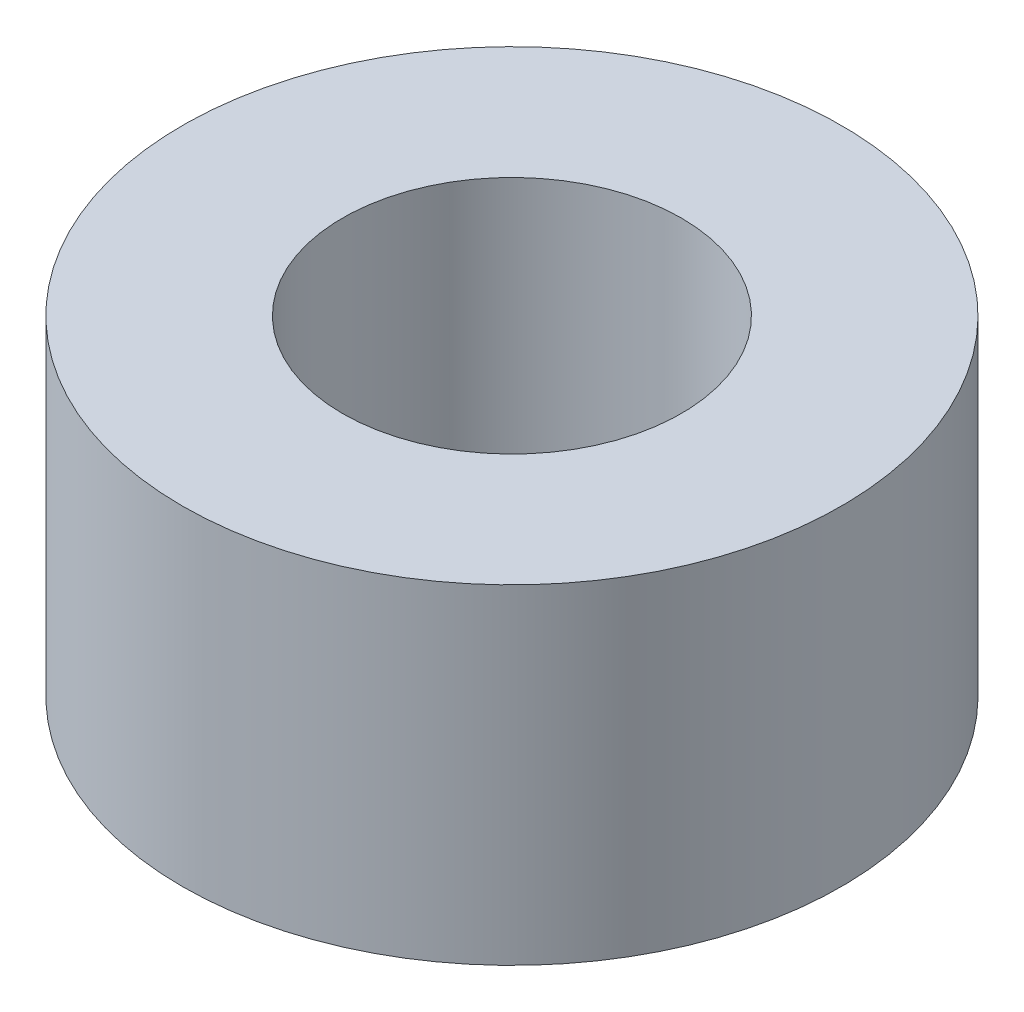
SolidWorks part; units mm, degrees
material "Plain Carbon Steel"
ref_plane "Front Plane" through (0, 0, 0) normal (0, 0, 1) x (1, 0, 0)
ref_plane "Top Plane" through (0, 0, 0) normal (0, 1, 0) x (1, 0, 0)
ref_plane "Right Plane" through (0, 0, 0) normal (1, 0, 0) x (0, 0, -1)
sketch "Sketch1" plane through (0, 0, 0) normal (0, 1, 0) x (1, 0, 0)
  circle A0 centre (0, 0) radius 6.35
  circle A1 centre (0, 0) radius 3.2639
  dimension "D1" = 12.7
  dimension "D2" = 6.5278
extrude "Boss-Extrude1" add sketch "Sketch1" along normal blind 6.35
